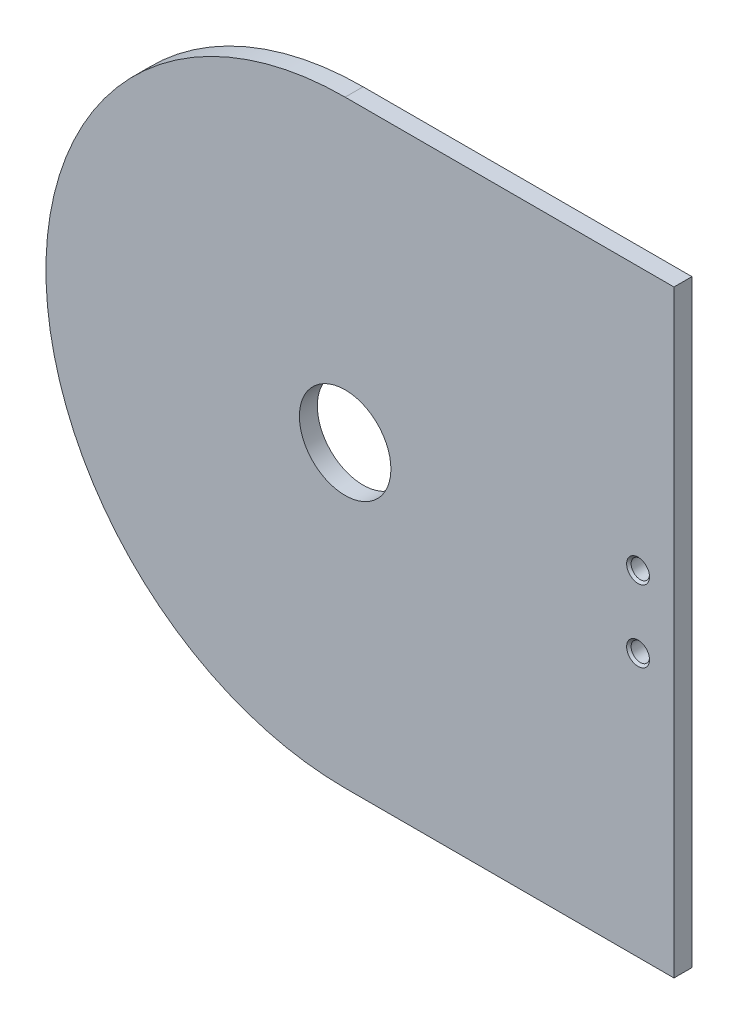
SolidWorks part; units mm, degrees
material "ABS"
ref_plane "前视基准面" through (0, 0, 0) normal (0, 0, 1) x (1, 0, 0)
ref_plane "上视基准面" through (0, 0, 0) normal (0, 1, 0) x (1, 0, 0)
ref_plane "右视基准面" through (0, 0, 0) normal (1, 0, 0) x (0, 0, -1)
sketch "草图1" plane through (0, 0, 0) normal (0, 1, 0) x (1, 0, 0)
  line L1 (-25, -50) -> (25, -50)
  line L2 (-25, -50) -> (-25, 50)
  line L3 (-25, 50) -> (25, 50)
  line L4 (25, -50) -> (25, 50)
  line L5 (-25, -50) -> (25, 50) construction
  line L6 (-25, 50) -> (25, -50) construction
  point P0 (0, 0)
  dimension "D1" = 100
  dimension "D2" = 50
extrude "凸台-拉伸1" add sketch "草图1" along normal blind 2
sketch "草图2" plane through (0, 2, 0) normal (0, 1, 0) x (1, 0, 0)
  line L0 (-25, -50) -> (25, -50) construction
  line L1 (-25, 50) -> (-22, 50)
  line L2 (-25, 50) -> (-25, -50)
  line L3 (-25, -50) -> (-22, -50)
  line L4 (-22, 50) -> (-22, -50)
  dimension "D1" = 3
extrude "凸台-拉伸2" add sketch "草图2" along normal blind 80
sketch "草图3" plane through (-25, 0, 0) normal (-1, 0, 0) x (0, 0, 1)
  line L1 (-50, 82) -> (-48, 82)
  line L2 (-50, 82) -> (-50, 15.3)
  line L3 (-50, 15.3) -> (-48, 15.3)
  line L4 (-48, 82) -> (-48, 15.3)
  dimension "D1" = 66.7
  dimension "D2" = 2
extrude "凸台-拉伸3" add sketch "草图3" along normal blind 70 contours L4 L3 L2 L1
sketch "草图4" plane through (0, 0, -50) normal (0, 0, -1) x (-1, 0, 0)
  line L2 (61.65, 82) -> (95, 82)
  line L3 (95, 82) -> (95, 48.65)
  line L4 (61.65, 15.3) -> (95, 15.3)
  line L5 (95, 15.3) -> (95, 48.65)
  line L6 (22, 82) -> (95, 82) construction
  arc A1 (61.65, 82) -> (95, 48.65) centre (61.65, 48.65) cw
  arc A2 (95, 48.65) -> (61.65, 15.3) centre (61.65, 48.65) cw
  point P17 (95, 48.65)
  line M4 (95, 15.3) -> (95, 82)
  line M5 (95, 82) -> (22, 82)
  dimension "D1" = 33.35
extrude "切除-拉伸4" cut sketch "草图4" against normal up to next contours A1 M5 M4 | A2 L4 L5
sketch "草图8" plane through (-25, 0, 0) normal (-1, 0, 0) x (0, 0, 1)
  line L0 (-48, 82) -> (50, 82) construction
  line L1 (6, 82) -> (8, 82)
  line L2 (6, 82) -> (6, 15.3)
  line L3 (6, 15.3) -> (8, 15.3)
  line L4 (8, 82) -> (8, 15.3)
  line L5 (50, 82) -> (50, 0) construction
  dimension "D1" = 42
  dimension "D2" = 66.7
  dimension "D3" = 2
extrude "凸台-拉伸4" add sketch "草图8" along normal blind 70 contours L2 L3 L4 L1
sketch "草图9" plane through (0, 0, 8) normal (0, 0, 1) x (1, 0, 0)
  line L0 (-61.65, 82) -> (-95, 82)
  line L1 (-95, 48.65) -> (-95, 15.3)
  line L4 (-25, 15.3) -> (-25, 82)
  line L5 (-25, 82) -> (-95, 82)
  line L6 (-95, 82) -> (-95, 15.3)
  line L7 (-95, 15.3) -> (-25, 15.3)
  line L8 (-25, 15.3) -> (-25, 82)
  line L9 (-25, 82) -> (-95, 82)
  line L10 (-95, 82) -> (-95, 15.3)
  line L11 (-95, 15.3) -> (-25, 15.3)
  arc A0 (-61.65, 82) -> (-61.65, 15.3) centre (-61.65, 48.65) ccw construction
  arc A1 (-61.65, 82) -> (-61.65, 15.3) centre (-61.65, 48.65) ccw
  dimension "D1" = 0
extrude "切除-拉伸5" cut sketch "草图9" against normal up to next contours L0 A1
sketch "草图10" plane through (0, 0, 8) normal (0, 0, 1) x (1, 0, 0)
  line L0 (-61.65, 48.65) -> (-61.65, 68.65) construction
  line L1 (-61.65, 48.65) -> (-44.3295, 38.65) construction
  line L2 (-61.65, 48.65) -> (-78.9705, 38.65) construction
  circle A0 centre (-61.65, 48.65) radius 20 construction
  point P7 (-61.65, 68.65)
  point P8 (-44.3295, 38.65)
  point P9 (-78.9705, 38.65)
  dimension "D1" = 40
  dimension "D2" = 120
  dimension "D3" = 120
hole_wizard "M3 螺纹孔1" positions "草图10" profile "草图11" tap size "M3" standard "GB"
sketch "草图11" plane through (-78.9705, 38.65, 8) normal (1, 0, 0) x (0, -1, 0)
  line L0 (0, 0) -> (0, 2)
  line L1 (0, 2) -> (1.25, 2)
  line L2 (1.25, 2) -> (1.25, 0.275)
  line L3 (1.25, 0.275) -> (1.525, 0)
  line L5 (1.525, 0) -> (0, 0)
  line L6 (-1.25, 0.275) -> (-1.525, 0) construction
  line L11 (0, -6.35) -> (0, 107.95) construction
  dimension "通孔螺纹孔钻头直径" = 2.5
  dimension "通孔螺纹孔钻头深度" = 2
  dimension "近端锥形沉头孔直径" = 3.05
  dimension "近端锥形沉头孔角度" = 90
cosmetic thread "孔螺纹线5" parameters "D2"=3
cosmetic thread "孔螺纹线6" parameters "D2"=3
cosmetic thread "孔螺纹线7" parameters "D2"=3
fillet "圆角1" radius 2 3 edges at (-23.5, 82, 50) (25, 1, -50) (25, 1, 50)
sketch "草图12" plane through (0, 0, 8) normal (0, 0, 1) x (1, 0, 0)
  circle A0 centre (-61.65, 48.65) radius 11
  dimension "D1" = 22
extrude "切除-拉伸6" cut sketch "草图12" against normal up to next
sketch "草图13" plane through (0, 0, -50) normal (0, 0, -1) x (-1, 0, 0)
  circle A0 centre (61.65, 48.65) radius 14.5
  dimension "D1" = 29
extrude "切除-拉伸7" cut sketch "草图13" against normal up to next
sketch "草图14" plane through (-25, 0, 0) normal (-1, 0, 0) x (0, 0, 1)
  line L0 (-48, 82) -> (6, 82) construction
  line L1 (-39.5, 82) -> (-37.5, 82)
  line L2 (-39.5, 82) -> (-39.5, 15.3)
  line L3 (-39.5, 15.3) -> (-37.5, 15.3)
  line L4 (-37.5, 82) -> (-37.5, 15.3)
  line L5 (-50, 82) -> (-50, 15.3) construction
  dimension "D1" = 2
  dimension "D2" = 10.5
  dimension "D3" = 66.7
extrude "凸台-拉伸5" add sketch "草图14" along normal blind 70
sketch "草图15" plane through (0, 0, -39.5) normal (0, 0, -1) x (-1, 0, 0)
  line L0 (95, 82) -> (95, 15.3) construction
  line L1 (61.65, 15.3) -> (25, 15.3) construction
  circle A0 centre (61.65, 48.65) radius 5.1
  dimension "D1" = 10.2
  dimension "D2" = 33.35
  dimension "D3" = 33.35
extrude "切除-拉伸8" cut sketch "草图15" against normal up to next
sketch "草图18" plane through (0, 0, -39.5) normal (0, 0, -1) x (-1, 0, 0)
  line L0 (95, 82) -> (95, 15.3)
  line L1 (95, 15.3) -> (58.4851, 15.3)
  line L2 (95, 82) -> (58.4269, 82)
  arc A0 (61.65, 82) -> (95, 48.65) centre (61.65, 48.65) cw
  arc A1 (61.65, 15.3) -> (95, 48.65) centre (61.65, 48.65) ccw
  line M6 (95, 15.3) -> (95, 82)
  line M7 (95, 82) -> (25, 82)
  dimension "D1" = 33.35
  dimension "D2" = 33.35
extrude "切除-拉伸9" cut sketch "草图18" against normal through all and the other way through all contours A1 L1 M6 | A0 L0 M7
sketch "草图19" plane through (-25, 0, 0) normal (-1, 0, 0) x (0, 0, 1)
  line L1 (-50, 82) -> (-48, 82)
  line L2 (-50, 82) -> (-50, 15.3)
  line L3 (-50, 15.3) -> (-48, 15.3)
  line L4 (-48, 82) -> (-48, 15.3)
  dimension "D1" = 2
  dimension "D2" = 66.7
extrude "切除-拉伸10" cut sketch "草图19" along normal through all
fillet "圆角2" radius 2 1 edges at (-23.5, 82, -50)
sketch "草图20" plane through (0, 2, 0) normal (0, 1, 0) x (1, 0, 0)
  line L0 (-25, -8) -> (-95, -8)
  line L1 (-95, -8) -> (-95, -6)
  line L2 (-95, -6) -> (-25, -6)
  line L3 (-25, 37.5) -> (-25, -6) construction
  line L4 (-25, -6) -> (-25, 50)
  line L5 (-25, 50) -> (25, 50)
  line L6 (25, 50) -> (25, -50)
  line L7 (25, -50) -> (-25, -50)
  line L8 (-25, -50) -> (-25, -8)
  line L9 (25, -48) -> (25, 48) construction
  line L10 (-22, -50) -> (23, -50) construction
extrude "切除-拉伸11" cut sketch "草图20" against normal through all and the other way through all
sketch "草图21" plane through (0, 0, -37.5) normal (0, 0, 1) x (1, 0, 0)
  line L0 (-61.65, 48.65) -> (-5.0876, 48.65) construction
  line L1 (-29, 52.65) -> (-29, 44.65) construction
  line L2 (-25, 15.3) -> (-25, 82) construction
  point P8 (-29, 44.65)
  point P9 (-29, 52.65)
  dimension "D1" = 8
  dimension "D2" = 4
hole_wizard "M2.5 螺纹孔1" positions "草图21" profile "草图22" tap size "M2.5" standard "GB" end condition through all
sketch "草图22" plane through (-29, 52.65, -37.5) normal (1, 0, 0) x (0, -1, 0)
  line L0 (0, 0) -> (0, 2)
  line L1 (0, 2) -> (1.025, 2)
  line L2 (1.025, 2) -> (1.025, 0.25)
  line L3 (1.025, 0.25) -> (1.275, 0)
  line L5 (1.275, 0) -> (0, 0)
  line L6 (-1.025, 0.25) -> (-1.275, 0) construction
  line L11 (0, -6.35) -> (0, 107.95) construction
  dimension "通孔螺纹孔钻头直径" = 2.05
  dimension "通孔螺纹孔钻头深度" = 2
  dimension "近端锥形沉头孔直径" = 2.55
  dimension "近端锥形沉头孔角度" = 90
